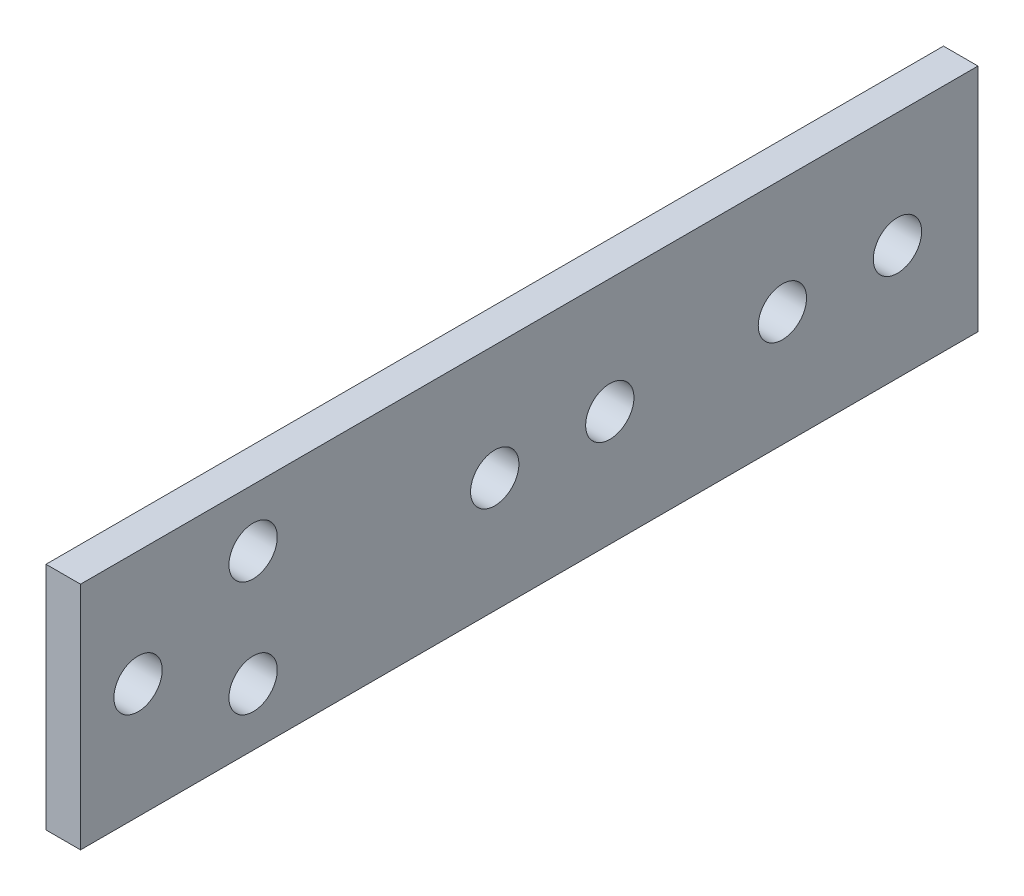
SolidWorks part; units mm, degrees
ref_plane "前视基准面" through (0, 0, 0) normal (0, 0, 1) x (1, 0, 0)
ref_plane "上视基准面" through (0, 0, 0) normal (0, 1, 0) x (1, 0, 0)
ref_plane "右视基准面" through (0, 0, 0) normal (1, 0, 0) x (0, 0, -1)
ref_plane "基准面4" through (36, 0, 0) normal (1, 0, 0) x (0, 0, -1)
sketch "草图1" plane through (36, 0, 0) normal (1, 0, 0) x (0, 0, -1)
  line L0 (58, -60) -> (-20, -60)
  line L1 (-20, -60) -> (-20, -80)
  line L2 (-20, -80) -> (58, -80)
  line L3 (58, -80) -> (58, -60)
  circle A0 centre (-15, -70) radius 2.1
  circle A1 centre (41, -70) radius 2.1
  circle A2 centre (51, -70) radius 2.1
  circle A3 centre (26, -70) radius 2.1
  circle A4 centre (16, -70) radius 2.1
  circle A5 centre (-5, -65) radius 2.1
  circle A6 centre (-5, -75) radius 2.1
extrude "凸台-拉伸1" add sketch "草图1" against normal blind 3
